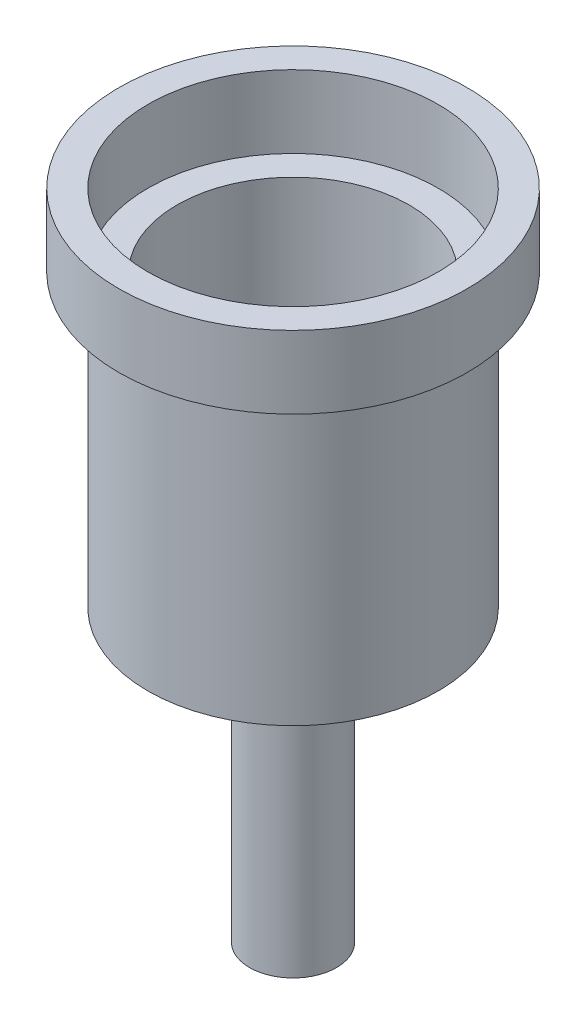
SolidWorks part; units mm, degrees
ref_plane "Front Plane" through (0, 0, 0) normal (0, 0, 1) x (1, 0, 0)
ref_plane "Top Plane" through (0, 0, 0) normal (0, 1, 0) x (1, 0, 0)
ref_plane "Right Plane" through (0, 0, 0) normal (1, 0, 0) x (0, 0, -1)
sketch "Sketch1" plane through (0, 0, 0) normal (0, 1, 0) x (1, 0, 0)
  circle A0 centre (0, 0) radius 1.905
  dimension "D1" = 3.81
extrude "Boss-Extrude1" add sketch "Sketch1" along normal blind 12.7 contours A0
sketch "Sketch2" plane through (0, 12.7, 0) normal (0, 1, 0) x (1, 0, 0)
  circle A0 centre (0, 0) radius 6.35
  dimension "D1" = 12.7
extrude "Boss-Extrude2" add sketch "Sketch2" along normal blind 12.7 contours A0
sketch "Sketch4" plane through (0, 25.4, 0) normal (0, 1, 0) x (1, 0, 0)
  circle A2 centre (0, 0) radius 5.08
extrude "Cut-Extrude2" cut sketch "Sketch4" against normal blind 10.16
sketch "Sketch5" plane through (0, 15.24, 0) normal (0, 1, 0) x (1, 0, 0)
  circle A0 centre (0, 0) radius 1.27
  dimension "D1" = 2.54
extrude "Cut-Extrude3" cut sketch "Sketch5" against normal blind 12.7
sketch "Sketch6" plane through (0, 0, 0) normal (1, 0, 0) x (0, 0, -1)
  line L0 (1.905, 0) -> (1.905, 12.7) construction
  line L1 (-1.27, 6.35) -> (1.27, 6.35)
  line L2 (-1.27, 6.35) -> (-1.27, 2.54)
  line L3 (-1.27, 2.54) -> (1.27, 2.54)
  line L4 (1.27, 6.35) -> (1.27, 2.54)
  line L6 (-1.905, 0) -> (1.905, 0) construction
  dimension "D1" = 3.81
  dimension "D2" = 2.54
  dimension "D3" = 0.635
  dimension "D4" = 2.54
extrude "Cut-Extrude4" cut sketch "Sketch6" against normal blind 5.08
sketch "Sketch7" plane through (0, 25.4, 0) normal (0, 1, 0) x (1, 0, 0)
  circle A0 centre (0, 0) radius 7.62
  circle A1 centre (0, 0) radius 6.35
  dimension "D1" = 15.24
extrude "Boss-Extrude3" add sketch "Sketch7" along normal blind 3.175
